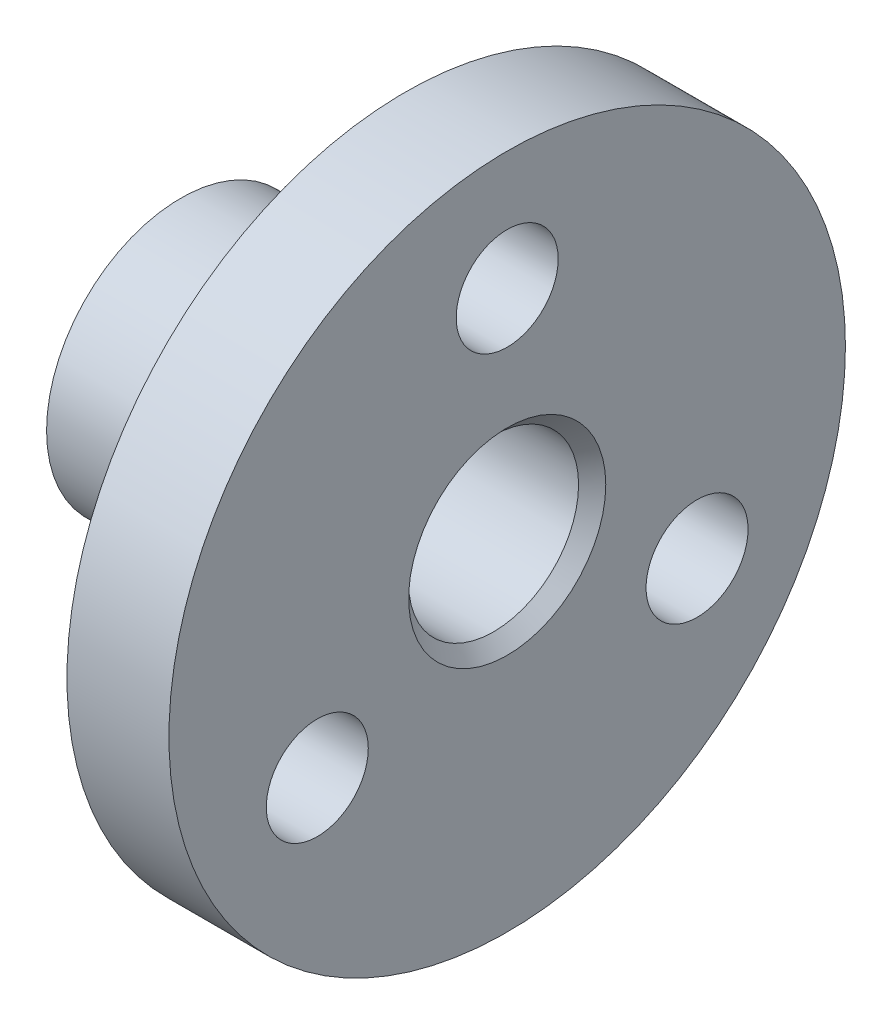
SolidWorks part; units mm, degrees
ref_plane "Спереди" through (0, 0, 0) normal (0, 0, 1) x (1, 0, 0)
ref_plane "Сверху" through (0, 0, 0) normal (0, 1, 0) x (1, 0, 0)
ref_plane "Справа" through (0, 0, 0) normal (1, 0, 0) x (0, 0, -1)
sketch "Эскиз1" plane through (0, 0, 0) normal (1, 0, 0) x (0, 0, -1)
  line L0 (0, 0) -> (0, 3.1459) construction
  circle A0 centre (0, 0) radius 9.95
  circle A1 centre (0, 6.45) radius 1.5
  circle A2 centre (5.5859, -3.225) radius 1.5
  circle A3 centre (-5.5859, -3.225) radius 1.5
  point P12 (0, 0)
  dimension "D1" = 19.9
  dimension "D2" = 3
  dimension "D3" = 6.45
  dimension "D4" = 3
extrude "Бобышка-Вытянуть1" add sketch "Эскиз1" along normal blind 3
sketch "Эскиз2" plane through (0, 0, 0) normal (-1, 0, 0) x (0, 0, 1)
  circle A0 centre (0, 0) radius 3.95
  dimension "D1" = 7.9
extrude "Бобышка-Вытянуть2" add sketch "Эскиз2" along normal blind 6.6
sketch "Эскиз3" plane through (-6.6, 0, 0) normal (-1, 0, 0) x (0, 0, 1)
  circle A0 centre (0, 0) radius 2.5
  dimension "D1" = 5
extrude "Вырез-Вытянуть1" cut sketch "Эскиз3" against normal through all both and the other way through all
chamfer "Фаска1" distance 0.4 angle 45 2 edges at (3, 0, 2.5) (-6.6, 0, 2.5)
